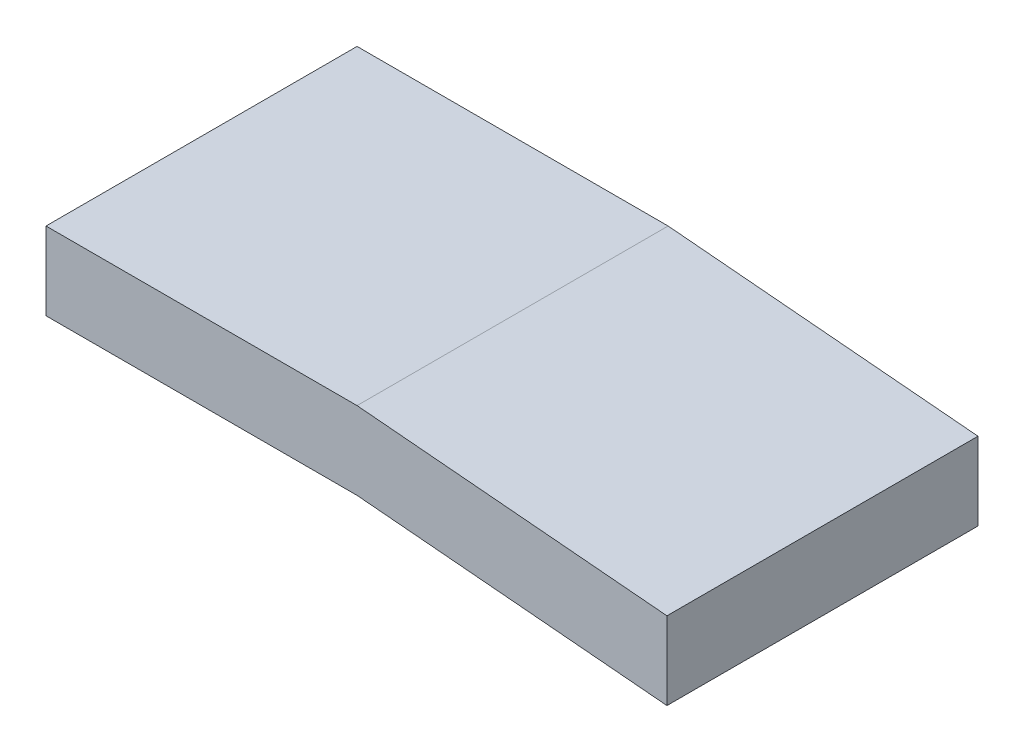
SolidWorks part; units mm, degrees
material "ASTM A500 Grade B Steel"
ref_plane "Front Plane" through (0, 0, 0) normal (0, 0, 1) x (1, 0, 0)
ref_plane "Top Plane" through (0, 0, 0) normal (0, 1, 0) x (1, 0, 0)
ref_plane "Right Plane" through (0, 0, 0) normal (1, 0, 0) x (0, 0, -1)
sketch "Sketch1" plane through (0, 0, 0) normal (0, 0, 1) x (1, 0, 0)
  line L0 (0, 0) -> (0, 12.7)
  line L1 (0, 12.7) -> (50.8, 12.7)
  line L2 (50.8, 12.7) -> (101.4067, 8.2725)
  line L3 (101.4067, 8.2725) -> (101.4067, -4.4275)
  line L4 (101.4067, -4.4275) -> (50.8, 0)
  line L5 (50.8, 0) -> (0, 0)
  point P7 (0, 0)
  point P8 (186.9265, -20.793)
  dimension "D1" = 175
  dimension "D2" = 50.8
  dimension "D3" = 50.8
  dimension "D4" = 12.7
extrude "Boss-Extrude1" add sketch "Sketch1" along normal blind 50.8
